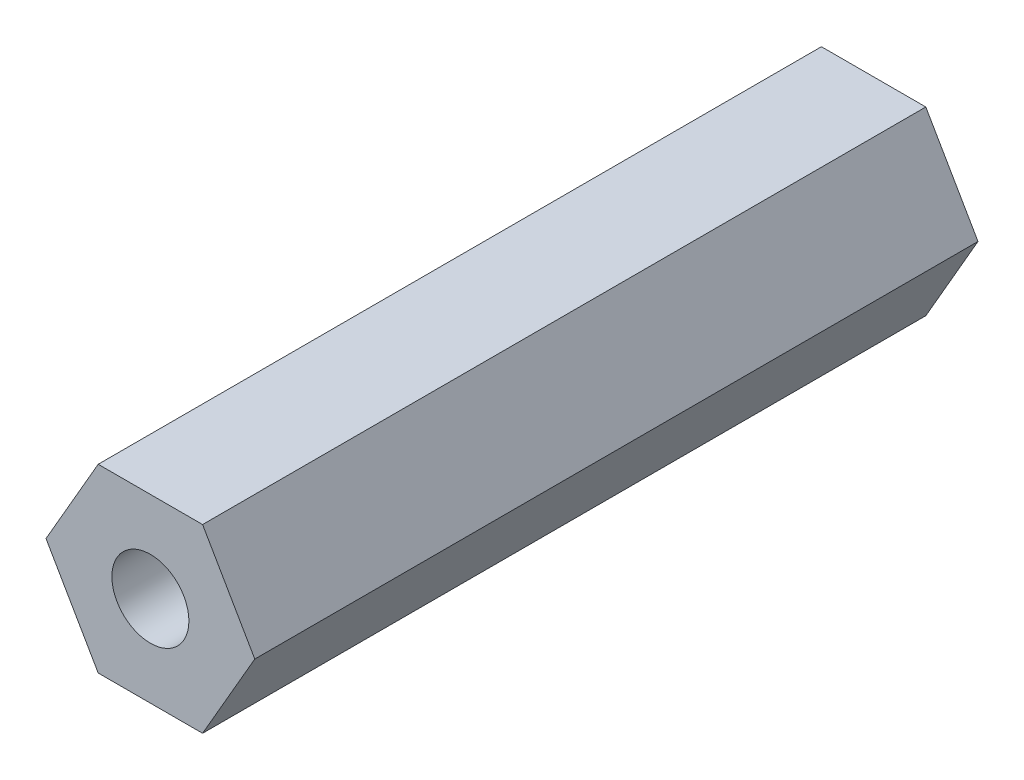
SolidWorks part; units mm, degrees
ref_plane "Front Plane" through (0, 0, 0) normal (0, 0, 1) x (1, 0, 0)
ref_plane "Top Plane" through (0, 0, 0) normal (0, 1, 0) x (1, 0, 0)
ref_plane "Right Plane" through (0, 0, 0) normal (1, 0, 0) x (0, 0, -1)
sketch "Sketch1" plane through (0, 0, 0) normal (0, 0, 1) x (1, 0, 0)
  line L1 (7.3323, 0) -> (3.6662, 6.35)
  line L2 (3.6662, 6.35) -> (-3.6662, 6.35)
  line L3 (-3.6662, 6.35) -> (-7.3323, 0)
  line L4 (-7.3323, 0) -> (-3.6662, -6.35)
  line L5 (-3.6662, -6.35) -> (3.6662, -6.35)
  line L6 (3.6662, -6.35) -> (7.3323, 0)
  circle A0 centre (0, 0) radius 6.35 construction
  dimension "D1" = 12.7
extrude "Boss-Extrude1" add sketch "Sketch1" along normal mid plane 50.8
hole_wizard "1/4-28 Tapped Hole1" positions "Sketch3" profile "Sketch2" tap size "1/4-28" standard "ANSI Inch"
sketch "Sketch3" plane through (0, 0, 25.4) normal (0, 0, 1) x (1, 0, 0)
  point P0 (0, 0)
sketch "Sketch2" plane through (0, 0, 25.4) normal (1, 0, 0) x (0, -1, 0)
  line L0 (0, 0) -> (0, 23.8504)
  line L1 (0, 23.8504) -> (2.7051, 22.225)
  line L2 (2.7051, 22.225) -> (2.7051, 0)
  line L5 (2.7051, 0) -> (0, 0)
  line L10 (0, 23.8504) -> (-2.7051, 22.225) construction
  line L11 (0, -6.35) -> (0, 107.95) construction
  dimension "Tap Drill Dia." = 5.4102
  dimension "Tap Drill Depth" = 22.225
  dimension "Drill Angle" = 118
hole_wizard "1/4-28 Tapped Hole2" positions "Sketch5" profile "Sketch4" tap size "1/4-28" standard "ANSI Inch"
sketch "Sketch5" plane through (0, 0, -25.4) normal (0, 0, -1) x (-1, 0, 0)
  point P0 (0, 0)
sketch "Sketch4" plane through (0, 0, -25.4) normal (1, 0, 0) x (0, 1, 0)
  line L0 (0, 0) -> (0, 23.8504)
  line L1 (0, 23.8504) -> (2.7051, 22.225)
  line L2 (2.7051, 22.225) -> (2.7051, 0)
  line L5 (2.7051, 0) -> (0, 0)
  line L10 (0, 23.8504) -> (-2.7051, 22.225) construction
  line L11 (0, -6.35) -> (0, 107.95) construction
  dimension "Tap Drill Dia." = 5.4102
  dimension "Tap Drill Depth" = 22.225
  dimension "Drill Angle" = 118
